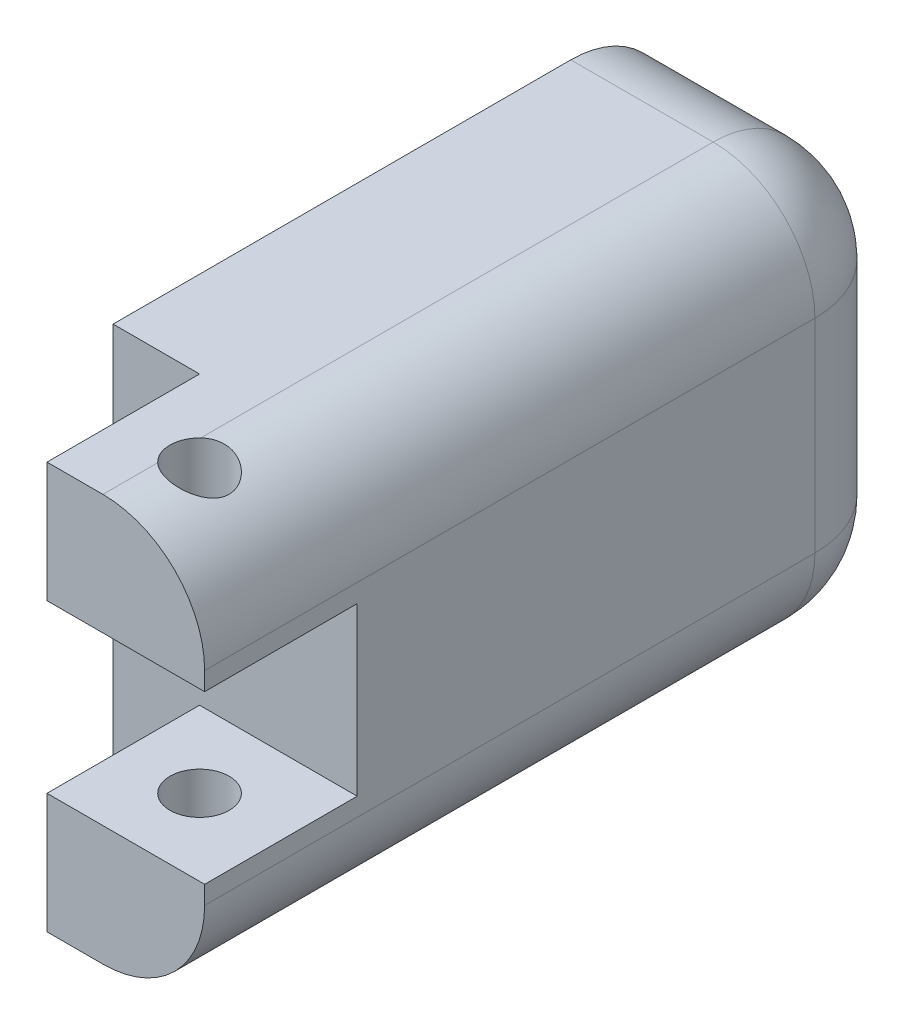
SolidWorks part; units mm, degrees
ref_plane "Спереди" through (0, 0, 0) normal (0, 0, 1) x (1, 0, 0)
ref_plane "Сверху" through (0, 0, 0) normal (0, 1, 0) x (1, 0, 0)
ref_plane "Справа" through (0, 0, 0) normal (1, 0, 0) x (0, 0, -1)
sketch "Эскиз1" plane through (0, 0, 0) normal (0, 1, 0) x (1, 0, 0)
  line L0 (-13, 27.5) -> (-13, 0)
  line L1 (-25, -7.5) -> (25, -7.5)
  line L2 (-25, -7.5) -> (-25, 27.5)
  line L3 (-25, 27.5) -> (-13, 27.5)
  line L4 (25, -7.5) -> (25, 27.5)
  line L5 (-25, -7.5) -> (25, 27.5) construction
  line L6 (-25, 27.5) -> (25, -7.5) construction
  line L7 (-13, 0) -> (13, 0)
  line L8 (13, 0) -> (13, 27.5)
  line L9 (13, 27.5) -> (25, 27.5)
  dimension "D1" = 27.5
  dimension "D2" = 50
  dimension "D3" = 26
  dimension "D4" = 35
extrude "Бобышка-Вытянуть1" add sketch "Эскиз1" along normal blind 20
fillet "Скругление1" radius 5 10 edges at (25, 0, -10) (25, 20, -10) (-25, 20, -10) (-25, 0, -10) (19, 20, -27.5) (25, 10, -27.5) (19, 0, -27.5) (-25, 10, -27.5) (-19, 20, -27.5) (-19, 0, -27.5)
sketch "Эскиз2" plane through (13, 0, 0) normal (-1, 0, 0) x (0, 0, 1)
  line L0 (-1030, 10) -> (48970, 10) construction
  line L1 (-27.5, 5) -> (-27.5, 15) construction
  circle A0 centre (-17.5, 10) radius 8
  point P5 (-27.5, 10)
  dimension "D1" = 16
  dimension "D2" = 10
extrude "Вырез-Вытянуть1" cut sketch "Эскиз2" against normal blind 5
sketch "Эскиз3" plane through (18, 0, 0) normal (-1, 0, 0) x (0, 0, 1)
  circle A0 centre (-17.5, 10) radius 6
  circle A1 centre (-17.5, 10) radius 8 construction
  dimension "D1" = 12
extrude "Вырез-Вытянуть2" cut sketch "Эскиз3" against normal blind 1
sketch "Эскиз4" plane through (-13, 0, 0) normal (1, 0, 0) x (0, 0, -1)
  line L0 (-1015, 10) -> (48985, 10) construction
  line L1 (-7.5, 15) -> (-7.5, 5) construction
  line L2 (13.195, 19.3021) -> (2.9, 14.5376)
  line L3 (2.9, 5.4624) -> (13.195, 0.6979)
  arc A0 (13.195, 0.6979) -> (13.195, 19.3021) centre (17.5, 10) ccw
  circle A1 centre (17.5, 10) radius 8 construction
  arc A2 (2.9, 14.5376) -> (2.9, 5.4624) centre (5, 10) ccw
  point P7 (-7.5, 10)
  dimension "D1" = 20.5
  dimension "D2" = 12.5
  dimension "D3" = 5
extrude "Вырез-Вытянуть3" cut sketch "Эскиз4" against normal blind 5
sketch "Эскиз5" plane through (-18, 0, 0) normal (1, 0, 0) x (0, 0, -1)
  line L0 (19.4, 15.8129) -> (19.4, 16.4984)
  line L1 (15.6, 16.4984) -> (15.6, 15.6654)
  line L2 (13.8328, 13.679) -> (1.9323, 12.2844)
  line L3 (1.9323, 7.7156) -> (13.8328, 6.321)
  line L4 (15.6, 4.3346) -> (15.6, 3.5016)
  line L5 (19.4, 3.5016) -> (19.4, 4.1871)
  arc A0 (19.4, 16.4984) -> (15.6, 16.4984) centre (17.5, 16.4984) ccw
  arc A1 (1.9323, 12.2844) -> (1.9323, 7.7156) centre (2.2, 10) ccw
  arc A2 (15.6, 3.5016) -> (19.4, 3.5016) centre (17.5, 3.5016) ccw
  arc A4 (20.2857, 14.1521) -> (20.2857, 5.8479) centre (17.5, 10) cw
  arc A5 (15.6, 4.3346) -> (13.8328, 6.321) centre (13.6, 4.3346) ccw
  arc A6 (15.6, 15.6654) -> (13.8328, 13.679) centre (13.6, 15.6654) cw
  arc A7 (20.2857, 5.8479) -> (19.4, 4.1871) centre (21.4, 4.1871) ccw
  arc A8 (20.2857, 14.1521) -> (19.4, 15.8129) centre (21.4, 15.8129) cw
  arc A9 (15.25, 20) -> (13.195, 19.3021) centre (17.5, 10) ccw construction
  arc A10 (15.25, 20) -> (13.195, 19.3021) centre (17.5, 10) ccw construction
  dimension "D3" = 2.3
  dimension "D4" = 1.9
  dimension "D5" = 5
  dimension "D8" = 2
  dimension "D9" = 2
  dimension "D1" = 3.8
  dimension "D2" = 15.3
  dimension "D6" = 12.9968
  dimension "D7" = 0.833
extrude "Вырез-Вытянуть4" cut sketch "Эскиз5" against normal blind 5
sketch "Эскиз6" plane through (-23, 0, 0) normal (1, 0, 0) x (0, 0, -1)
  line L0 (-990.222, 10) -> (49009.778, 10) construction
  line L1 (22.5, 5) -> (22.5, 15) construction
  line L2 (17.5, -985.0921) -> (17.5, 49014.9079) construction
  circle A0 centre (2.278, 10) radius 0.625
  circle A1 centre (6.3111, 10) radius 0.625
  circle A2 centre (10.4282, 10) radius 0.625
  circle A3 centre (17.5, 14.9079) radius 0.625
  circle A4 centre (17.5, 16.8489) radius 0.625
  circle A5 centre (17.5, 5.0821) radius 0.625
  circle A6 centre (17.5, 3.1411) radius 0.625
  point P11 (24009.778, 10)
  point P14 (22.5, 10)
  dimension "D1" = 1.25
  dimension "D2" = 4.0331
  dimension "D3" = 4.1171
  dimension "D4" = 12.0718
  dimension "D5" = 4.9079
  dimension "D6" = 1.9409
  dimension "D7" = 4.9179
  dimension "D8" = 1.9409
  dimension "D9" = 5
extrude "Вырез-Вытянуть5" cut sketch "Эскиз6" against normal blind 4
sketch "Эскиз7" plane through (0, 0, 7.5) normal (0, 0, 1) x (1, 0, 0)
  line L0 (-20, 20) -> (20, 20) construction
  line L1 (-13.5, 20) -> (13.5, 20)
  line L2 (-13.5, 20) -> (-13.5, 15)
  line L3 (-13.5, 15) -> (13.5, 15)
  line L4 (13.5, 20) -> (13.5, 15)
  line L5 (-25, 15) -> (-25, 5) construction
  line L6 (25, 15) -> (25, 5) construction
  line L7 (-20, 0) -> (20, 0) construction
  line L8 (-13.5, 0) -> (13.5, 0)
  line L9 (-13.5, 0) -> (-13.5, 5)
  line L10 (-13.5, 5) -> (13.5, 5)
  line L11 (13.5, 0) -> (13.5, 5)
  dimension "D1" = 11.5
  dimension "D2" = 11.5
  dimension "D3" = 5
extrude "Вырез-Вытянуть6" cut sketch "Эскиз7" against normal blind 7
sketch "Эскиз8" plane through (0, 15, 0) normal (0, 1, 0) x (1, 0, 0)
  line L0 (-1013.5, -4) -> (48986.5, -4) construction
  line L1 (-13.5, -0.5) -> (-13.5, -7.5) construction
  line L2 (-13.5, -0.5) -> (-13.5, -7.5) construction
  line L3 (13.5, -0.5) -> (13.5, -7.5) construction
  circle A0 centre (-8.5, -4) radius 1.45
  circle A1 centre (8.5, -4) radius 1.45
  point P9 (-13.5, -4)
  dimension "D1" = 5
  dimension "D2" = 2.9
  dimension "D3" = 5
extrude "Вырез-Вытянуть7" cut sketch "Эскиз8" against normal blind 12
sketch "Эскиз9" plane through (0, 0, 0) normal (0, -1, 0) x (1, 0, 0)
  line L0 (13, 0) -> (17.25, 0)
  line L1 (17.25, 7.5) -> (-36.6834, 12.0491)
  line L2 (13.5, 7.5) -> (20, 7.5) construction
  line L3 (-36.6834, 12.0491) -> (-29.5799, -33.3513)
  line L4 (-29.5799, -33.3513) -> (-5.1811, -33.3513)
  line L5 (-5.1811, -33.3513) -> (8.2022, -2.2608)
  line L6 (8.2022, -2.2608) -> (13, 0)
  line L7 (17.25, 0) -> (17.25, 7.5)
  dimension "D1" = 4.25
extrude "Вырез-Вытянуть8" cut sketch "Эскиз9" against normal through all
sketch "Эскиз10" plane through (17.25, 0, 0) normal (-1, 0, 0) x (0, 0, 1)
  line L0 (7.5, 20) -> (7.5, 0) construction
  line L1 (7.5, 14.1) -> (0, 14.1)
  line L2 (7.5, 14.1) -> (7.5, 5.9)
  line L3 (7.5, 5.9) -> (0, 5.9)
  line L4 (0, 14.1) -> (0, 5.9)
  line L5 (0, 20) -> (0, 0) construction
  line L6 (0, 20) -> (7.5, 20) construction
  line L7 (0, 0) -> (7.5, 0) construction
  dimension "D1" = 5.9
  dimension "D2" = 5.9
extrude "Вырез-Вытянуть9" cut sketch "Эскиз10" against normal through all
sketch "Эскиз11" plane through (0, 5.9, 0) normal (0, 1, 0) x (1, 0, 0)
  line L0 (-982.75, -3.75) -> (49017.25, -3.75) construction
  line L2 (21, -1005.4877) -> (21, 48994.5123) construction
  line L4 (20, -7.5) -> (25, -7.5) construction
  line L5 (25, 22.5) -> (25, -7.5) construction
  circle A0 centre (21, -3.75) radius 1.455
  dimension "D3" = 2.91
  dimension "D1" = 3.75
  dimension "D2" = 4
extrude "Вырез-Вытянуть10" cut sketch "Эскиз11" against normal through all both and the other way through all
